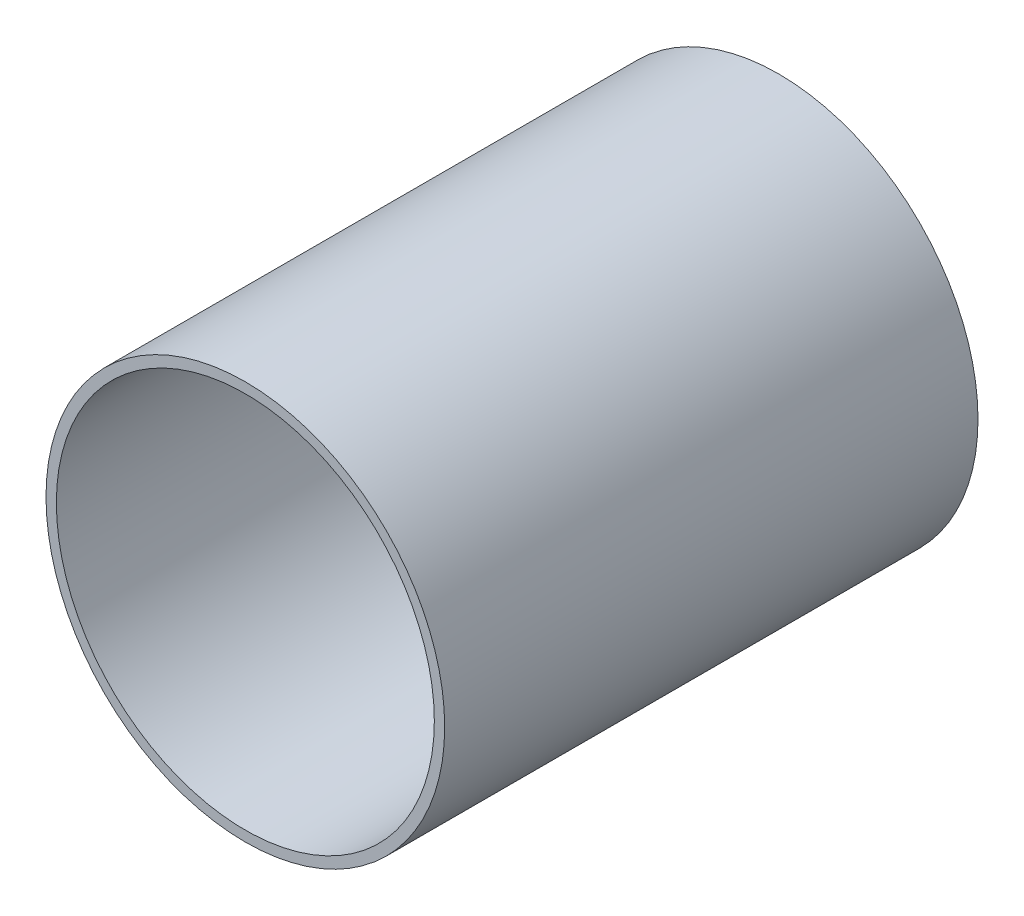
SolidWorks part; units mm, degrees
ref_plane "Plano frontal" through (0, 0, 0) normal (0, 0, 1) x (1, 0, 0)
ref_plane "Plano superior" through (0, 0, 0) normal (0, 1, 0) x (1, 0, 0)
ref_plane "Plano direito" through (0, 0, 0) normal (1, 0, 0) x (0, 0, -1)
sketch "Esboço1" plane through (0, 0, 0) normal (0, 0, 1) x (1, 0, 0)
  line L0 (0, 0) -> (0, 3.5776) construction
  circle A0 centre (0, 0) radius 3.65
  circle A1 centre (0, 0) radius 3.85
  dimension "D1" = 7.3
  dimension "D2" = 0.2
extrude "Ressalto-extrusão1" add sketch "Esboço1" along normal blind 10.3
